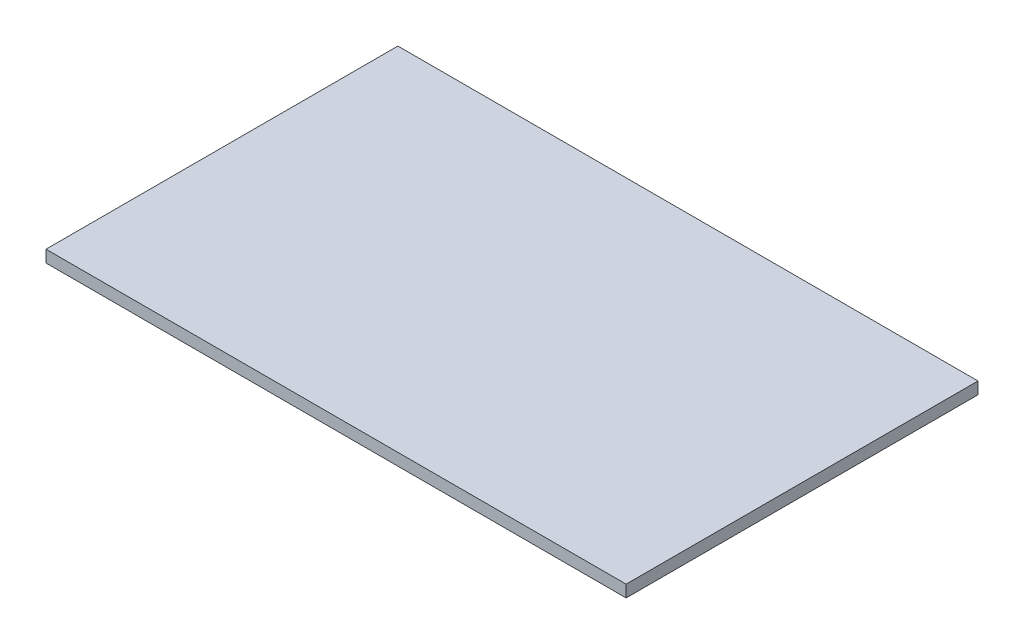
SolidWorks part; units mm, degrees
ref_plane "Plano frontal" through (0, 0, 0) normal (0, 0, 1) x (1, 0, 0)
ref_plane "Plano superior" through (0, 0, 0) normal (0, 1, 0) x (1, 0, 0)
ref_plane "Plano direito" through (0, 0, 0) normal (1, 0, 0) x (0, 0, -1)
sketch "Esboço1" plane through (0, 0, 0) normal (0, 1, 0) x (1, 0, 0)
  line L1 (0, 0) -> (61, 0)
  line L2 (0, 0) -> (0, 37)
  line L3 (0, 37) -> (61, 37)
  line L4 (61, 0) -> (61, 37)
  dimension "D1" = 37
  dimension "D2" = 61
extrude "Ressalto-extrusão1" add sketch "Esboço1" along normal blind 1.26
